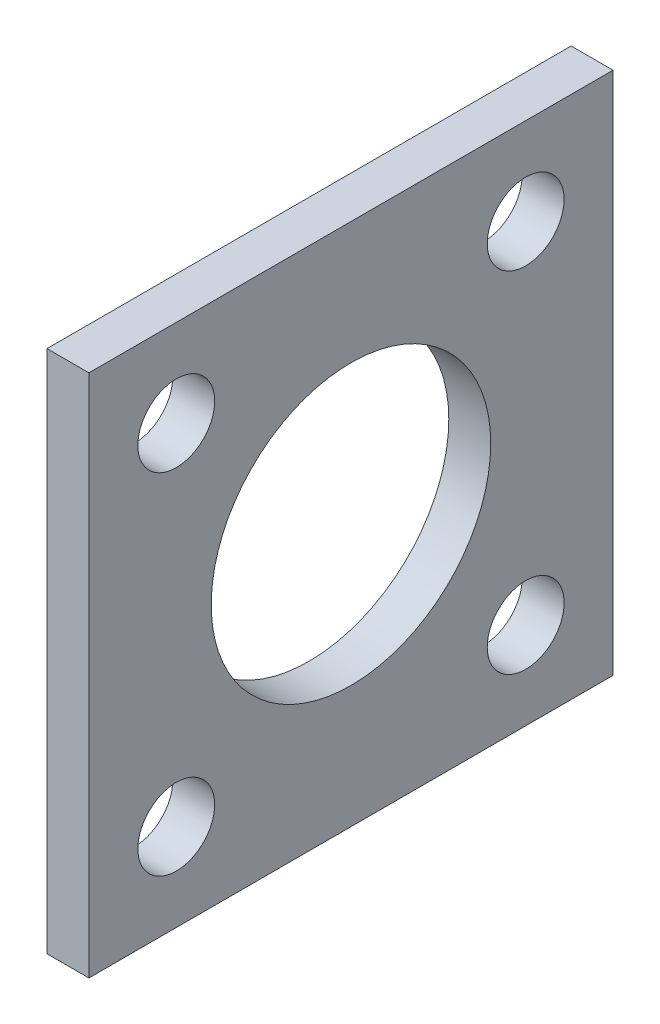
SolidWorks part; units mm, degrees
ref_plane "Front Plane" through (0, 0, 0) normal (0, 0, 1) x (1, 0, 0)
ref_plane "Top Plane" through (0, 0, 0) normal (0, 1, 0) x (1, 0, 0)
ref_plane "Right Plane" through (0, 0, 0) normal (1, 0, 0) x (0, 0, -1)
sketch "Sketch1" plane through (0, 0, 0) normal (1, 0, 0) x (0, 0, -1)
  line L0 (0, 0) -> (0, 37.5) construction
  line L1 (-37.5, 37.5) -> (37.5, 37.5)
  line L2 (-37.5, 37.5) -> (-37.5, -37.5)
  line L3 (-37.5, -37.5) -> (37.5, -37.5)
  line L4 (37.5, 37.5) -> (37.5, -37.5)
  line L5 (-37.5, 37.5) -> (37.5, -37.5) construction
  line L6 (-37.5, -37.5) -> (37.5, 37.5) construction
  line L7 (0, 0) -> (-37.5, 0) construction
  circle A0 centre (25, 25) radius 5.5
  circle A1 centre (-25, 25) radius 5.5
  circle A2 centre (25, -25) radius 5.5
  circle A3 centre (-25, -25) radius 5.5
  circle A4 centre (0, 0) radius 20
  point P0 (0, 0)
  dimension "D3" = 11
  dimension "D1" = 75
  dimension "D2" = 75
  dimension "D4" = 25
  dimension "D5" = 25
extrude "Boss-Extrude1" add sketch "Sketch1" along normal blind 6
